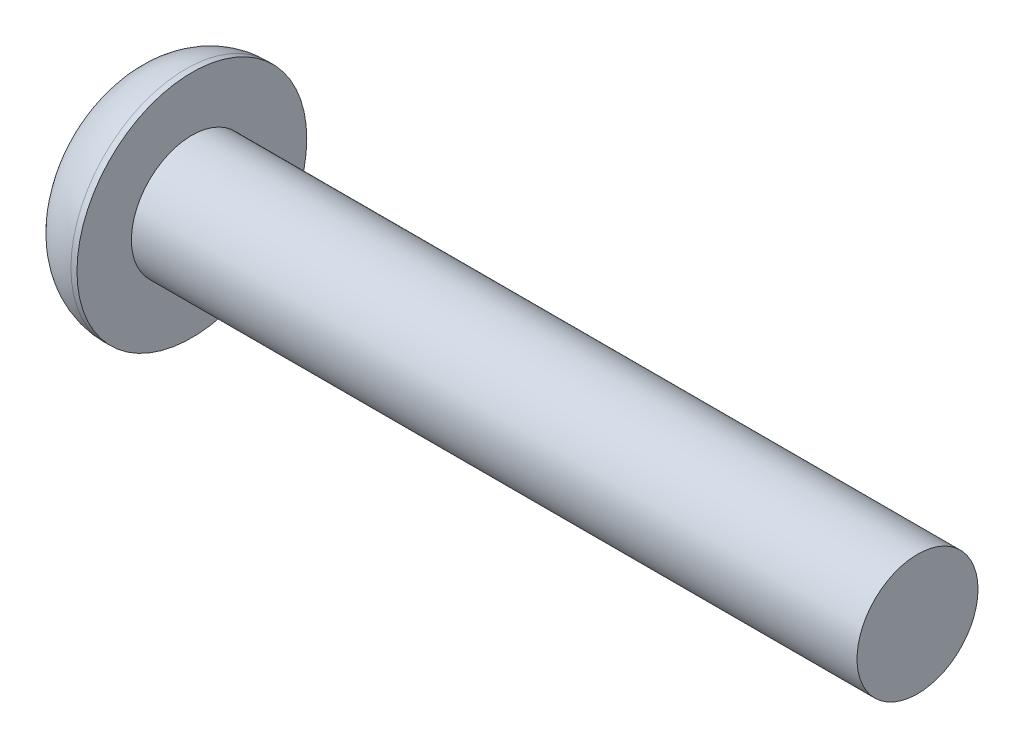
SolidWorks part; units mm, degrees
material "AISI 1020"
ref_plane "Front Plane" through (0, 0, 0) normal (0, 0, 1) x (1, 0, 0)
ref_plane "Top Plane" through (0, 0, 0) normal (0, 1, 0) x (1, 0, 0)
ref_plane "Right Plane" through (0, 0, 0) normal (1, 0, 0) x (0, 0, -1)
sketch "Sketch1" plane through (0, 0, 0) normal (0, 1, 0) x (1, 0, 0)
  line L0 (0, 0) -> (19.65, 0)
  line L1 (19.65, 0) -> (19.65, 1.5)
  line L2 (19.65, 1.5) -> (1.65, 1.5)
  line L3 (1.65, 1.5) -> (1.65, 2.85)
  line L4 (1.65, 2.85) -> (1.5, 2.85)
  line L5 (0, 1.35) -> (0, 0)
  line L6 (0, 0) -> (-8.9321, 0) construction
  arc A0 (0, 1.35) -> (1.5, 2.85) centre (1.5, 1.35) cw
  point P11 (0, 2.85)
  dimension "D5" = 1.5
  dimension "D1" = 1.5
  dimension "D2" = 18
  dimension "D3" = 1.65
  dimension "D4" = 2.85
revolve "Revolve1" add sketch "Sketch1" angle 360 about L6
sketch "Sketch2" plane through (0, 0, 0) normal (-1, 0, 0) x (0, 0, 1)
  line L1 (1.1547, 0) -> (0.5774, 1)
  line L2 (0.5774, 1) -> (-0.5774, 1)
  line L3 (-0.5774, 1) -> (-1.1547, 0)
  line L4 (-1.1547, 0) -> (-0.5774, -1)
  line L5 (-0.5774, -1) -> (0.5774, -1)
  line L6 (0.5774, -1) -> (1.1547, 0)
  circle A0 centre (0, 0) radius 1 construction
  dimension "D1" = 2
extrude "Cut-Extrude1" cut sketch "Sketch2" against normal blind 1.04
